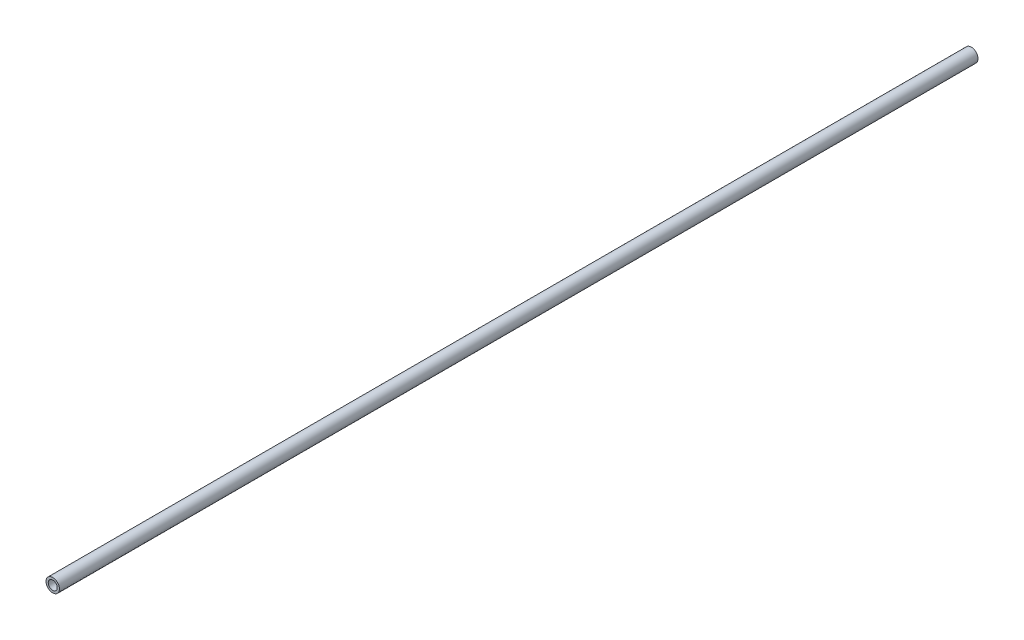
SolidWorks part; units mm, degrees
material "CarbonFiber"
ref_plane "Спереди" through (0, 0, 0) normal (0, 0, 1) x (1, 0, 0)
ref_plane "Сверху" through (0, 0, 0) normal (0, 1, 0) x (1, 0, 0)
ref_plane "Справа" through (0, 0, 0) normal (1, 0, 0) x (0, 0, -1)
sketch "Эскиз1" plane through (0, 0, 0) normal (0, 0, 1) x (1, 0, 0)
  circle A0 centre (0, 0) radius 3
  circle A1 centre (0, 0) radius 2
  dimension "D1" = 6
  dimension "D2" = 1
extrude "Бобышка-Вытянуть1" add sketch "Эскиз1" along normal mid plane 410
equation "\"DTailTube\"= 16mm'Диаметр трубки хвостового оперения"
equation "\"FusLenght\"= 700mm"
equation "\"DMotor\"= 35.2mm"
equation "\"MotorArm\"= 320mm"
equation "\"DFus\"= 150mm"
equation "\"DFusTube\"= 30mm'Диаметр трубки внутри фюзеляжа"
equation "\"FusTubeHeight\"= 40mm"
equation "\"FusCentralPartLenght\"= 410mm"
equation "\"FusNoseLenght\"= 150mm"
equation "\"WingOffset\"= 1mm'Расстояние от внутренней поверхности фюзеляжа до профиля крыла по вертикали"
equation "\"EllipseRatio\"= 0.95'Центральная часть фюзеляжа - эллипс. Этот параметр - отношение длин осей эллипса"
equation "\"FrameOffset\"= 0.6mm"
equation "\"DThreadedInsert\"= 3.6mm'Внешний диамер резьбовых втулок"
equation "\"CenterSectionLenght\"= 140mm'Длина центроплана"
equation "\"b\"= 1700mm'Размах"
equation "\"cwr\"= 236mm'Корневая хорда крыла"
equation "\"TR\"= 0.75'Сужение крыла"
equation "\"cwt\"= \"TR\" * \"cwr\"'Концевая хорда крыла"
equation "\"DWingMainSpar\"= 16mm'Диаметр главного лонжерона крыла"
equation "\"DWingSecondSpar\"= 8mm'Диаметр второго лонжерона крыла"
equation "\"WingSparsDistance\"= 80mm'Расстояния между отверстиями по лонжерон крыла"
equation "\"c\"= 210mm'САХ крыла"
equation "\"FusTubeLenght\"= \"FusLenght\"-50mm'Длина трубки фюзеляжа"
equation "\"bt\"=291mm'Высота лопатки хвоста"
equation "\"TailTubeLenght\"=730mm'Длина хвостовой балки"
equation "\"DStringer\"=6mm'Диаметр стрингеров"
equation "\"D1@Эскиз1\"=\"DStringer\""
equation "\"D1@Бобышка-Вытянуть1\"=\"FusCentralPartLenght\""
equation "\"TailConnectorBaseLenght\"=20mm'Высота основания конектора хвоста"
equation "\"CargoHolderHoleDistance\"=30mm'Расстояние между крепежными отверстиями для держателя груза"
equation "\"FuselageThickness\"=1.2mm'Толщина фюзеляжа"
equation "\"ct\"=182mm'Корневая хорда хвоста"
equation "\"lambda_t\"=0.3'Доля хвоста, занатая рулем высоты"
equation "\"DTailSpar\"=6mm'Диаметр лонжерона хвостового оперения"
equation "\"TailSparDistance\"=40mm'Расстояние между лонжеронами хвостового оперения"
equation "\"CrossSectionWidth\"=15mm'Ширина кольцевой части шпангоута"
